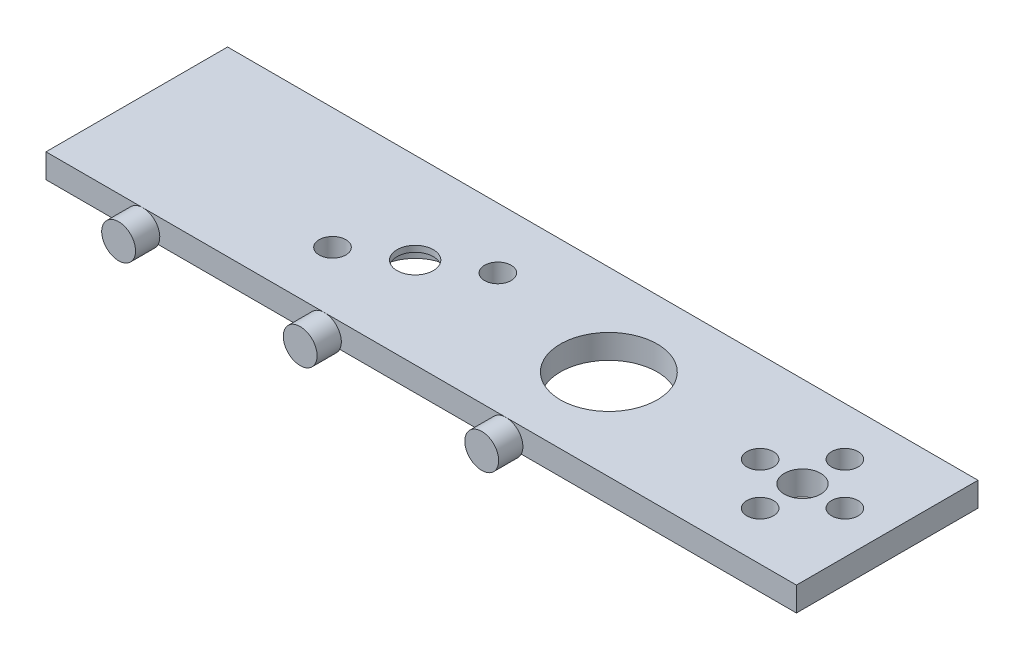
SolidWorks part; units mm, degrees
ref_plane "前视基准面" through (0, 0, 0) normal (0, 0, 1) x (1, 0, 0)
ref_plane "上视基准面" through (0, 0, 0) normal (0, 1, 0) x (1, 0, 0)
ref_plane "右视基准面" through (0, 0, 0) normal (1, 0, 0) x (0, 0, -1)
other "Configuration Table"
sketch "草图1" plane through (0, 0, 0) normal (0, 1, 0) x (1, 0, 0)
  line L0 (-31, 7.5) -> (31, 7.5)
  line L1 (31, 7.5) -> (31, -7.5)
  line L2 (31, -7.5) -> (-31, -7.5)
  line L3 (-31, -7.5) -> (-31, 7.5)
  line L4 (-31, 0) -> (31, 0) construction
  line L5 (-12.3301, -2.5) -> (-3.6699, 2.5) construction
  line L6 (-12.8083, -5.95) -> (-3.1917, -5.95) construction
  line L7 (-12.8083, 5.95) -> (-3.1917, 5.95) construction
  line L8 (-8, 0) -> (-8, 4.4384) construction
  circle A0 centre (-8, 0) radius 1.5
  circle A1 centre (-3.6699, 2.5) radius 1.1
  circle A3 centre (-12.3301, -2.5) radius 1.1
  arc A4 (-12.8083, 5.95) -> (-12.8083, -5.95) centre (-8, 0) ccw construction
  circle A5 centre (8, 0) radius 4
  arc A6 (-3.1917, -5.95) -> (-3.1917, 5.95) centre (-8, 0) ccw construction
  circle A7 centre (24, 0) radius 1.5
  circle A8 centre (24, 0) radius 3.5 construction
  circle A9 centre (27.5, 0) radius 1.1
  circle A10 centre (24, -3.5) radius 1.1
  circle A11 centre (20.5, 0) radius 1.1
  circle A12 centre (24, 3.5) radius 1.1
  circle A13 centre (-3.6699, -2.5) radius 1.1
  circle A14 centre (-12.3301, 2.5) radius 1.1
  point P5 (0, 7.5)
  point P7 (-31, 0)
  dimension "D3" = 3
  dimension "D6" = 2.2
  dimension "D9" = 15.3
  dimension "D12" = 8
  dimension "D14" = 3
  dimension "D15" = 7
  dimension "D16" = 2.2
  dimension "D1" = 62
  dimension "D2" = 15
  dimension "D4" = 23
  dimension "D7" = 30
  dimension "D8" = 10
  dimension "D10" = 11.9
  dimension "D11" = 16
  dimension "D13" = 16
  dimension "D5" = 2
  dimension "D17" = 4
extrude "凸台-拉伸1" add sketch "草图1" along normal blind 2 contours A3 | L3 L2 L1 L0 A13 A12 A11 A10 A9 A7 A5 A3 A1 A0 A14 | A1
sketch "草图2" plane through (0, 0, 7.5) normal (0, 0, 1) x (1, 0, 0)
  line L0 (-31, 0.6) -> (31, 0.6) construction
  line L1 (-31, 2) -> (-31, 0) construction
  line L3 (31, 2) -> (-31, 2) construction
  circle A0 centre (-23, 0.6) radius 1.4
  circle A1 centre (-8, 0.6) radius 1.4
  circle A2 centre (7, 0.6) radius 1.4
  dimension "D1" = 2.8
  dimension "D2" = 2.8
  dimension "D3" = 2.8
  dimension "D4" = 15
  dimension "D5" = 15
  dimension "D6" = 8
  dimension "D7" = 1.4
extrude "凸台-拉伸2" add sketch "草图2" along normal blind 2
sketch "草图3" plane through (0, 0, 0) normal (0, -1, 0) x (1, 0, 0)
  circle A0 centre (-8, 0) radius 3
  dimension "D1" = 6
extrude "切除-拉伸1" cut sketch "草图3" against normal blind 1.5
